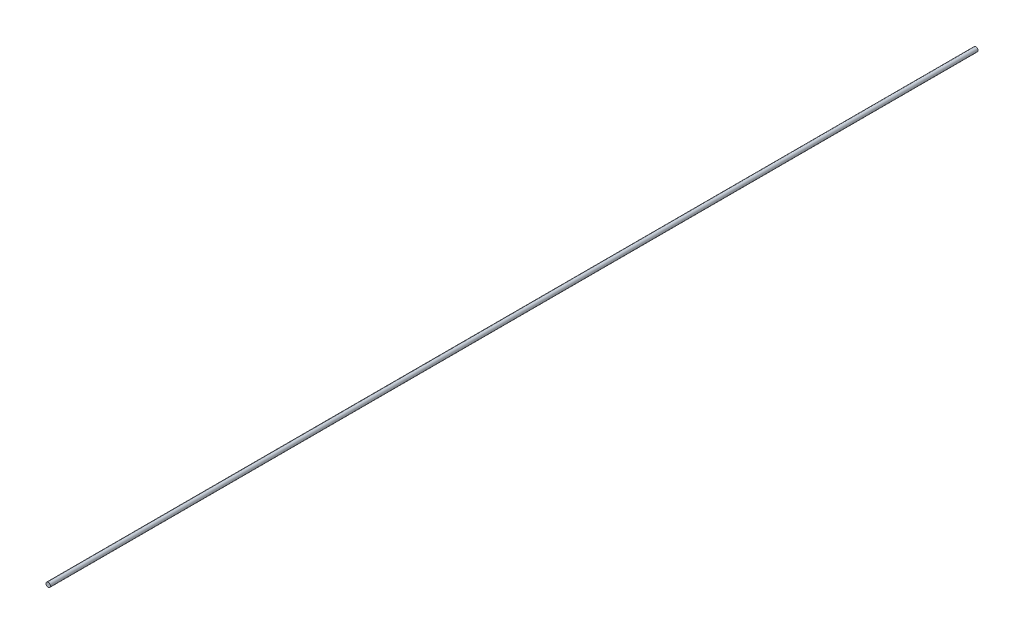
SolidWorks part; units mm, degrees
ref_plane "前视基准面" through (0, 0, 0) normal (0, 0, 1) x (1, 0, 0)
ref_plane "上视基准面" through (0, 0, 0) normal (0, 1, 0) x (1, 0, 0)
ref_plane "右视基准面" through (0, 0, 0) normal (1, 0, 0) x (0, 0, -1)
other "Configuration Table"
sketch "草图1" plane through (0, 0, 0) normal (0, 0, 1) x (1, 0, 0)
  circle A0 centre (0, 0) radius 0.4
extrude "D0p8钢索直线跨度" add sketch "草图1" along normal blind 169.6641
